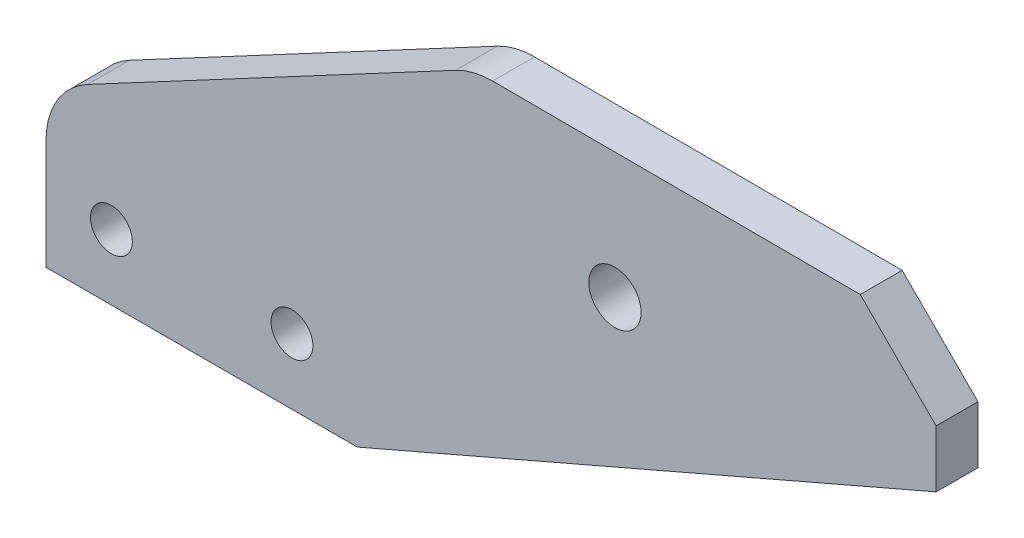
SolidWorks part; units mm, degrees
ref_plane "Front Plane" through (0, 0, 0) normal (0, 0, 1) x (1, 0, 0)
ref_plane "Top Plane" through (0, 0, 0) normal (0, 1, 0) x (1, 0, 0)
ref_plane "Right Plane" through (0, 0, 0) normal (1, 0, 0) x (0, 0, -1)
sketch "Sketch1" plane through (0, 0, 0) normal (0, 0, 1) x (1, 0, 0)
  line L0 (0, 0) -> (0, 10.6678)
  line L1 (0, -55) -> (0, 55) construction
  line L2 (0, 0) -> (30.226, 0)
  line L3 (55, 0) -> (-55, 0) construction
  line L5 (86.4102, 29.8737) -> (79.0464, 37.2375)
  line L6 (79.0464, 37.2375) -> (43.363, 37.3378)
  line L7 (39.756, 36.4415) -> (4.0343, 17.3915)
  line L8 (30.226, 0) -> (30.226, 31.3308) construction
  line L9 (79.0464, 37.2375) -> (79.0464, 25.9956) construction
  line L10 (30.226, 0) -> (86.4102, 24.3253)
  line L11 (86.4102, 24.3253) -> (86.4102, 29.8737)
  line L12 (86.4102, 24.3253) -> (86.4102, 9.5094) construction
  line L13 (86.4102, 9.5094) -> (55.4248, 9.5094) construction
  line L14 (55.4248, 9.5094) -> (55.4248, 16.1689) construction
  arc A0 (39.756, 36.4415) -> (43.363, 37.3378) centre (43.3416, 29.7179) cw
  arc A1 (0, 10.6678) -> (4.0343, 17.3915) centre (7.62, 10.6678) cw
  circle A2 centre (6.35, 6.35) radius 2.032
  circle A3 centre (23.876, 6.35) radius 2.032
  circle A6 centre (55.2306, 25.0861) radius 2.54
  point P21 (41.4468, 37.3432)
  point P24 (0, 15.24)
  dimension "D9" = 7.62
  dimension "D11" = 4.064
  dimension "D12" = 6.35
  dimension "D13" = 6.35
  dimension "D14" = 4.064
  dimension "D15" = 6.35
  dimension "D16" = 6.35
  dimension "D19" = 5.08
  dimension "D1" = 15.24
  dimension "D2" = 30.226
  dimension "D3" = 61.2241
  dimension "D4" = 10.414
  dimension "D5" = 5.5484
  dimension "D6" = 135.161
  dimension "D7" = 37.5996
  dimension "D8" = 46.9722
  dimension "D10" = 86.4102
  dimension "D17" = 30.9855
  dimension "D18" = 30.9855
extrude "Boss-Extrude1" add sketch "Sketch1" along normal blind 4.064
